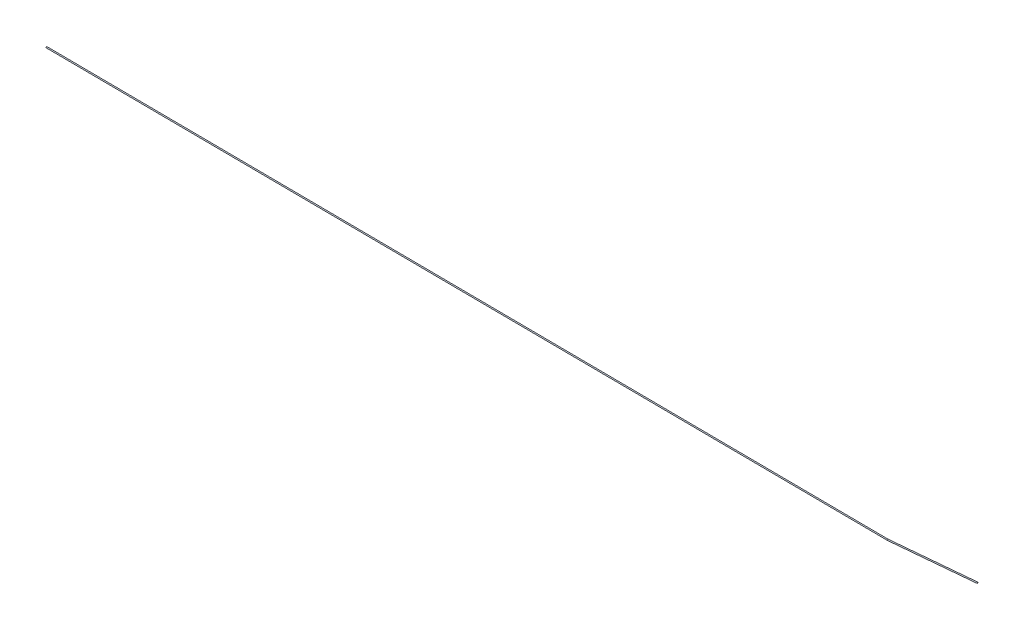
SolidWorks part; units mm, degrees
material "Nickel"
ref_plane "Front Plane" through (0, 0, 0) normal (0, 0, 1) x (1, 0, 0)
ref_plane "Top Plane" through (0, 0, 0) normal (0, 1, 0) x (1, 0, 0)
ref_plane "Right Plane" through (0, 0, 0) normal (1, 0, 0) x (0, 0, -1)
sketch3d "3DSketch1"
  line L0 (-599.875, 90.0518, 68.1263) -> (63.6981, 84.4528, 67.2672)
  line L1 (63.6981, 84.4528, 67.2672) -> (128.9834, 85.023, 61.8009)
sweep "Sweep1" add path "3DSketch1" circular profile diameter 0.82 parameters "D3"=0.82
